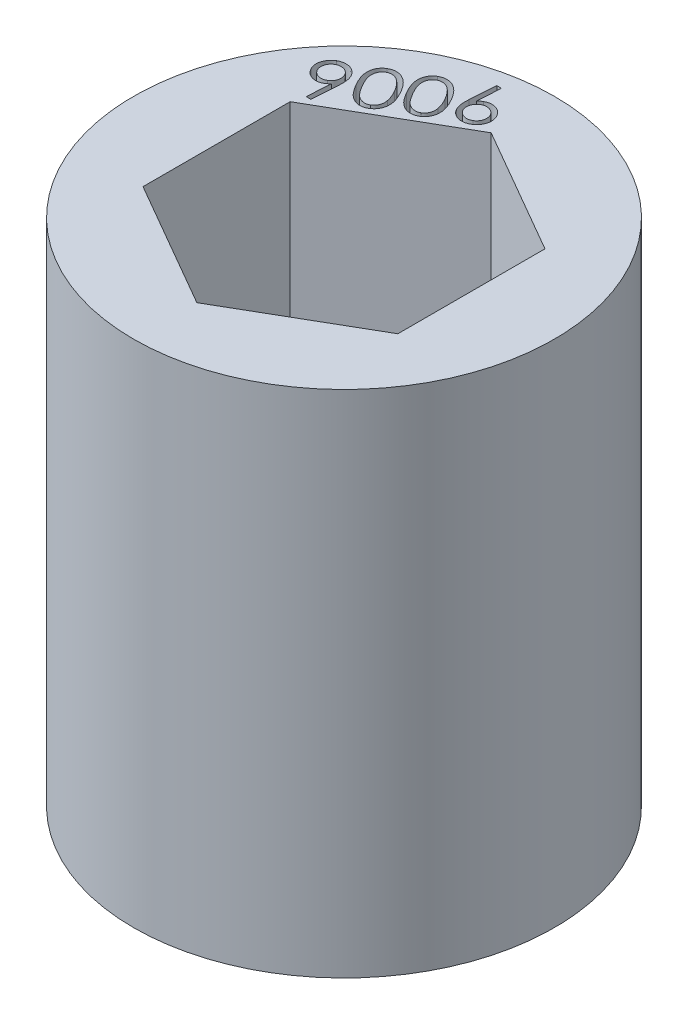
SolidWorks part; units mm, degrees
material "ABS"
ref_plane "Front Plane" through (0, 0, 0) normal (0, 0, 1) x (1, 0, 0)
ref_plane "Top Plane" through (0, 0, 0) normal (0, 1, 0) x (1, 0, 0)
ref_plane "Right Plane" through (0, 0, 0) normal (1, 0, 0) x (0, 0, -1)
sketch "Sketch1" plane through (0, 0, 0) normal (0, 1, 0) x (1, 0, 0)
  line L1 (0, 7.7723) -> (-6.731, 3.8861)
  line L2 (-6.731, 3.8861) -> (-6.731, -3.8861)
  line L3 (-6.731, -3.8861) -> (0, -7.7723)
  line L4 (0, -7.7723) -> (6.731, -3.8861)
  line L5 (6.731, -3.8861) -> (6.731, 3.8861)
  line L6 (6.731, 3.8861) -> (0, 7.7723)
  circle A0 centre (0, 0) radius 11.1125
  circle A1 centre (0, 0) radius 6.731 construction
  dimension "D1" = 22.225
  dimension "D2" = 13.462
extrude "Boss-Extrude1" add sketch "Sketch1" along normal blind 26.924
sketch "Sketch2" plane through (0, 26.924, 0) normal (0, 1, 0) x (1, 0, 0)
  line L0 (-6.909, 4.2527) -> (-0.2563, 8.0936) construction
  line L1 (0, 7.7723) -> (-6.731, 3.8861) construction
  text T0 "9006" font "Century Gothic" height 2.54
  dimension "D1" = 0.4064
extrude "Cut-Extrude1" cut sketch "Sketch2" against normal blind 2
